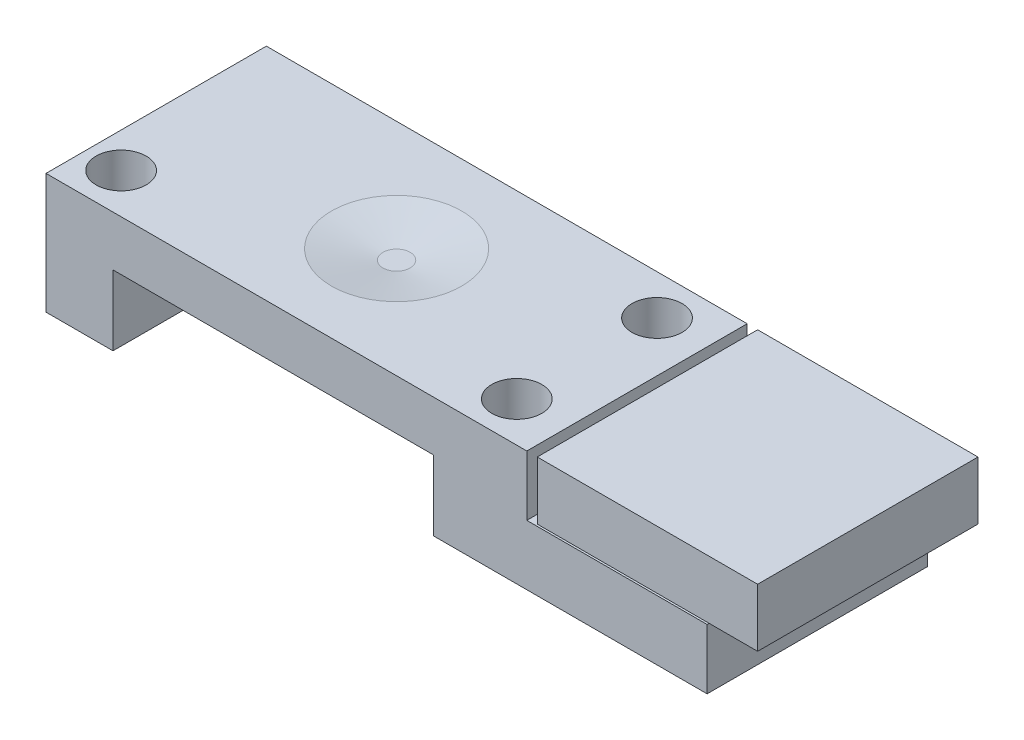
SolidWorks part; units mm, degrees
material "SUNTR"
ref_plane "Front Plane" through (0, 0, 0) normal (0, 0, 1) x (1, 0, 0)
ref_plane "Top Plane" through (0, 0, 0) normal (0, 1, 0) x (1, 0, 0)
ref_plane "Right Plane" through (0, 0, 0) normal (1, 0, 0) x (0, 0, -1)
sketch "Sketch1" plane through (0, 0, 0) normal (0, 0, 1) x (1, 0, 0)
  line L0 (19.3438, 0) -> (24, 0)
  line L1 (0, 0) -> (3.3438, 0)
  line L2 (0, 0) -> (0, 6)
  line L3 (0, 6) -> (24, 6)
  line L4 (24, 3) -> (24, 6)
  line L6 (3.3438, 0) -> (3.3438, 3.5)
  line L7 (3.3438, 3.5) -> (19.3438, 3.5)
  line L8 (19.3438, 0) -> (19.3438, 3.5)
  line L9 (24, 0) -> (33, 0)
  line L11 (24, 3) -> (33, 3)
  line L12 (33, 0) -> (33, 3)
  dimension "D1" = 24
  dimension "D2" = 6
  dimension "D3" = 16
  dimension "D4" = 9
  dimension "D5" = 3
  dimension "D6" = 3.5
extrude "Boss-Extrude1" add sketch "Sketch1" along normal blind 11
hole_wizard "Ø2.5 (2.5) Diameter Hole1" positions "Sketch3" profile "Sketch4" hole size "Ø2.5" standard "ANSI Metric" end condition through all
sketch "Sketch3" plane through (0, 6, 0) normal (0, 1, 0) x (1, 0, 0)
  line L0 (0, -5.5) -> (24, -5.5) construction
  line L1 (0, -11) -> (0, 0) construction
  line L2 (24, -11) -> (24, 0) construction
  line L4 (24, -11) -> (24, 0) construction
  point P0 (1.75, -9)
  point P2 (21.5, -2)
  point P4 (21.5, -9)
  dimension "D1" = 3.5
  dimension "D2" = 3.5
  dimension "D3" = 3.5
  dimension "D4" = 1.75
  dimension "D5" = 2.5
  dimension "D6" = 2.5
sketch "Sketch4" plane through (1.75, 6, 9) normal (1, 0, 0) x (0, 0, 1)
  line L0 (0, 0) -> (0, 6)
  line L1 (0, 6) -> (1.25, 6)
  line L2 (1.25, 6) -> (1.25, 0)
  line L5 (1.25, 0) -> (0, 0)
  line L11 (0, -6.35) -> (0, 107.95) construction
  dimension "Thru Hole Dia." = 2.5
  dimension "Thru Hole Depth" = 6
sketch "Sketch5" plane through (0, 0, 11) normal (0, 0, 1) x (1, 0, 0)
  line L1 (24.5211, 6) -> (35.5211, 6)
  line L2 (24.5211, 6) -> (24.5211, 3.1)
  line L3 (24.5211, 3.1) -> (35.5211, 3.1)
  line L4 (35.5211, 6) -> (35.5211, 3.1)
  line L5 (33, 3) -> (24, 3) construction
  dimension "D1" = 2.9
  dimension "D2" = 11
  dimension "D3" = 0.1
extrude "Boss-Extrude2" add sketch "Sketch5" against normal blind 11
sketch "Sketch6" plane through (0, 6, 0) normal (0, 1, 0) x (1, 0, 0)
  line L0 (12, 0) -> (12, -11) construction
  line L1 (24, 0) -> (0, 0) construction
  line L2 (24, -11) -> (0, -11) construction
  line L3 (0, -5.5) -> (24, -5.5) construction
  line L4 (0, -11) -> (0, 0) construction
  line L5 (24, -11) -> (24, 0) construction
  circle A0 centre (12, -5.5) radius 3.25
  dimension "D1" = 6.5
extrude "Cut-Extrude1" cut sketch "Sketch6" against normal blind 0.5 draft 79
